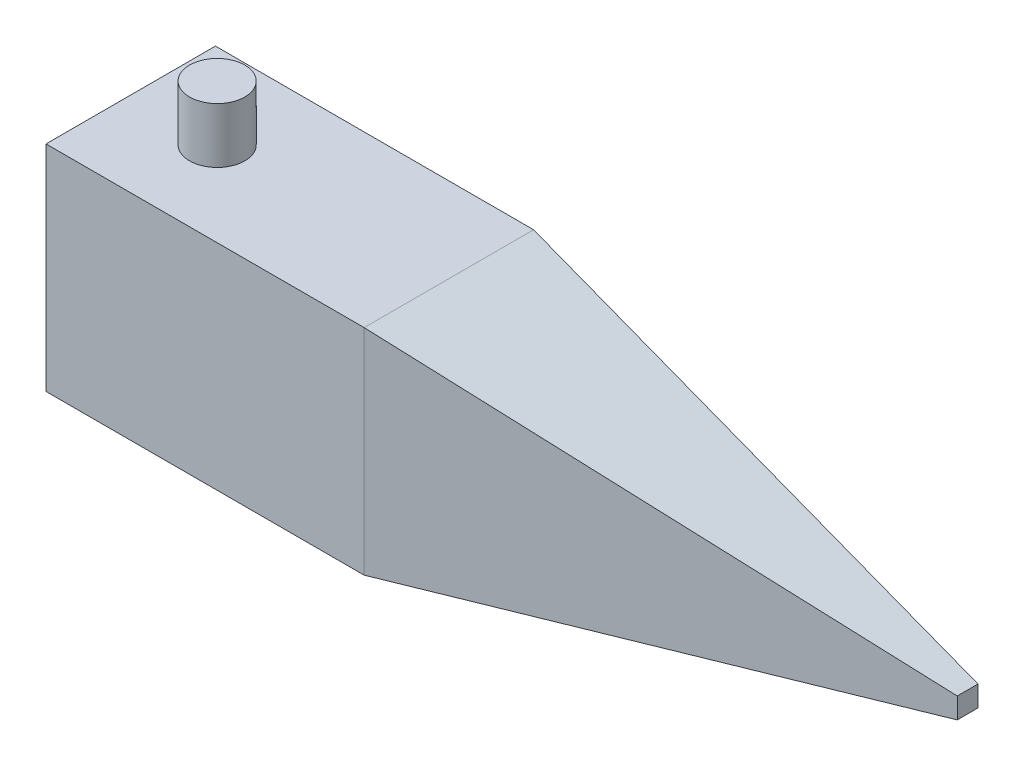
SolidWorks part; units mm, degrees
ref_plane "Front Plane" through (0, 0, 0) normal (0, 0, 1) x (1, 0, 0)
ref_plane "Top Plane" through (0, 0, 0) normal (0, 1, 0) x (1, 0, 0)
ref_plane "Right Plane" through (0, 0, 0) normal (1, 0, 0) x (0, 0, -1)
sketch "Sketch1" plane through (0, 0, 0) normal (0, 1, 0) x (1, 0, 0)
  line L1 (-23, -12.25) -> (23, -12.25)
  line L2 (-23, -12.25) -> (-23, 12.25)
  line L3 (-23, 12.25) -> (23, 12.25)
  line L4 (23, -12.25) -> (23, 12.25)
  line L5 (-23, -12.25) -> (23, 12.25) construction
  line L6 (-23, 12.25) -> (23, -12.25) construction
  point P0 (0, 0)
  dimension "D1" = 24.5
  dimension "D2" = 46
extrude "Body" add sketch "Sketch1" along normal blind 31
sketch "Sketch3" plane through (0, 0, 0) normal (0, 1, 0) x (1, 0, 0)
  line L0 (-23, -12.25) -> (23, -12.25) construction
  line L1 (-21, 10.25) -> (21, 10.25)
  line L2 (-21, 10.25) -> (-21, -10.25)
  line L3 (-21, -10.25) -> (21, -10.25)
  line L4 (21, 10.25) -> (21, -10.25)
  line L5 (-21, 10.25) -> (21, -10.25) construction
  line L6 (-21, -10.25) -> (21, 10.25) construction
  line L7 (23, -12.25) -> (23, 12.25) construction
  point P0 (0, 0)
  dimension "D1" = 2
  dimension "D2" = 2
extrude "Servo Hole" cut sketch "Sketch3" along normal blind 29
ref_plane "Point plane" through (98, 0, 0) normal (1, 0, 0) x (0, 0, -1)
sketch "Point" plane through (98, 0, 0) normal (1, 0, 0) x (0, 0, -1)
  line L1 (-1.5, 14) -> (1.5, 14)
  line L2 (-1.5, 14) -> (-1.5, 17)
  line L3 (-1.5, 17) -> (1.5, 17)
  line L4 (1.5, 14) -> (1.5, 17)
  line L5 (-1.5, 14) -> (1.5, 17) construction
  line L6 (-1.5, 17) -> (1.5, 14) construction
  line L8 (12.25, 31) -> (-12.25, 0) construction
  point P0 (0, 15.5)
  dimension "D1" = 3
  dimension "D2" = 3
loft "Loft1" add profiles "Point" section "Point" section face at (23, 15.5, 0)
sketch "Sketch5" plane through (-23, 0, 0) normal (-1, 0, 0) x (0, 0, 1)
  line L8 (-6, 27) -> (6, 27)
  line L13 (6, 27) -> (6, 22)
  line L14 (6, 22) -> (4.5, 22)
  line L17 (4.5, 22) -> (4.5, 2)
  line L18 (4.5, 2) -> (-4.5, 2)
  line L19 (-12.25, 0) -> (12.25, 0) construction
  line L21 (-4.5, 2) -> (-4.5, 22)
  line L22 (-4.5, 22) -> (-6, 22)
  line L23 (-6, 22) -> (-6, 27)
  line L25 (-12.25, 31) -> (12.25, 31) construction
  dimension "D1" = 4
  dimension "D2" = 2
  dimension "D3" = 5
  dimension "D4" = 12
  dimension "D5" = 5
  dimension "D6" = 1.5
  dimension "D7" = 1.5
  dimension "D8" = 4.5
extrude "Cut-Extrude3" cut sketch "Sketch5" against normal blind 29
sketch "Sketch6" plane through (0, 31, 0) normal (0, 1, 0) x (1, 0, 0)
  line L2 (-10.5, 0) -> (0, 0) construction
  line L3 (-23, 12.25) -> (-23, -12.25) construction
  circle A0 centre (-10.5, 0) radius 4
  point P3 (-23, 0)
  dimension "D2" = 8
  dimension "D1" = 12.5
extrude "Boss-Extrude3" add sketch "Sketch6" along normal blind 8
